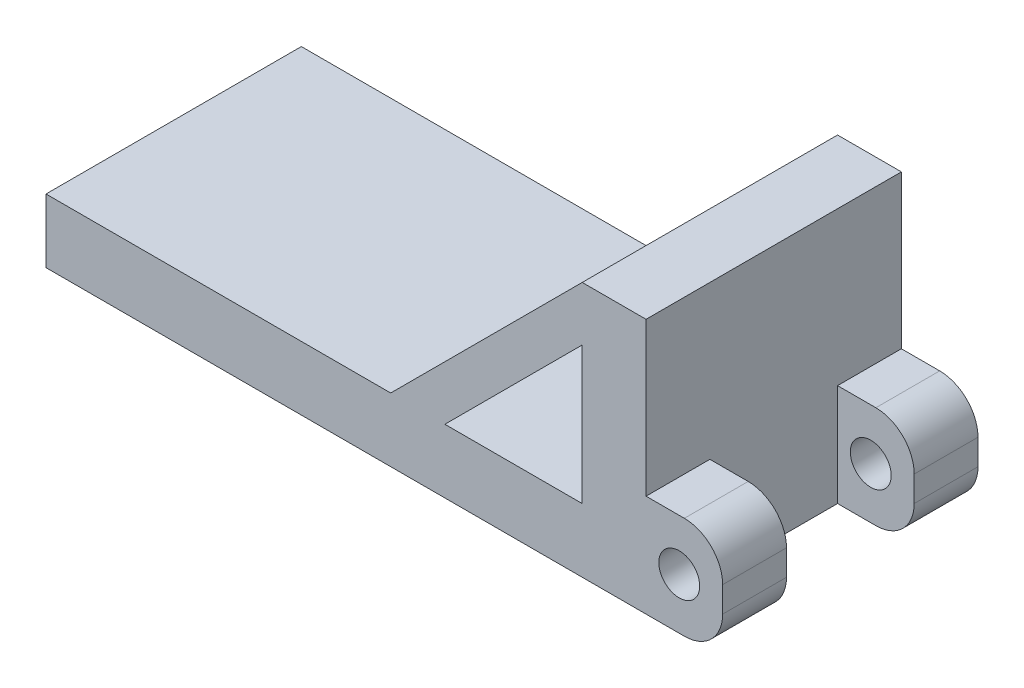
SolidWorks part; units mm, degrees
ref_plane "Front Plane" through (0, 0, 0) normal (0, 0, 1) x (1, 0, 0)
ref_plane "Top Plane" through (0, 0, 0) normal (0, 1, 0) x (1, 0, 0)
ref_plane "Right Plane" through (0, 0, 0) normal (1, 0, 0) x (0, 0, -1)
sketch "Sketch2" plane through (0, 0, 0) normal (0, 0, 1) x (1, 0, 0)
  line L0 (-45, 0) -> (0, 0)
  line L2 (2, 20) -> (-3, 20)
  line L4 (-3, 5) -> (-13.7574, 5)
  line L5 (-45, 5) -> (-45, 0)
  line L6 (-3, 20) -> (-18, 5)
  line L7 (0, 0) -> (8, 0)
  line L8 (-13.7574, 5) -> (-3, 15.7574)
  line L9 (-18, 5) -> (-45, 5)
  line L10 (-3, 15.7574) -> (-3, 5)
  line L11 (8, 0) -> (8, 8)
  line L12 (8, 8) -> (2, 8)
  line L13 (2, 8) -> (2, 20)
  line L14 (8, 4) -> (-3, 4) construction
  circle A0 centre (4.6, 4) radius 1.6
  point P12 (11.0806, 8)
  point P16 (2.6, 8.336)
  point P17 (12.2479, 3.2045)
  point P18 (6, 11.318)
  point P19 (0, 0)
  point P20 (0, 0)
  point P23 (0, 0)
  dimension "D2" = 3.2
  dimension "D9" = 2.6
  dimension "D1" = 45
  dimension "D3" = 45
  dimension "D4" = 5
  dimension "D5" = 5
  dimension "D6" = 3
  dimension "D7" = 20
  dimension "D8" = 8
  dimension "D10" = 6
  dimension "D11" = 8
extrude "Boss-Extrude1" add sketch "Sketch2" along normal blind 20
fillet "Fillet1" radius 3 2 edges at (8, 0, 10) (8, 8, 10)
sketch "Sketch3" plane through (0, 8, 0) normal (0, 1, 0) x (1, 0, 0)
  line L0 (2, -20) -> (2, 0) construction
  line L1 (2, -15) -> (2, -5)
  line L2 (2, -5) -> (8, -5)
  line L3 (8, 0) -> (8, -20) construction
  line L4 (8, -5) -> (8, -15)
  line L5 (8, -15) -> (2, -15)
  line L8 (2, -20) -> (2, 0) construction
  line L9 (2, -10) -> (8, -10) construction
  dimension "D1" = 10
extrude "Cut-Extrude1" cut sketch "Sketch3" against normal up to next
